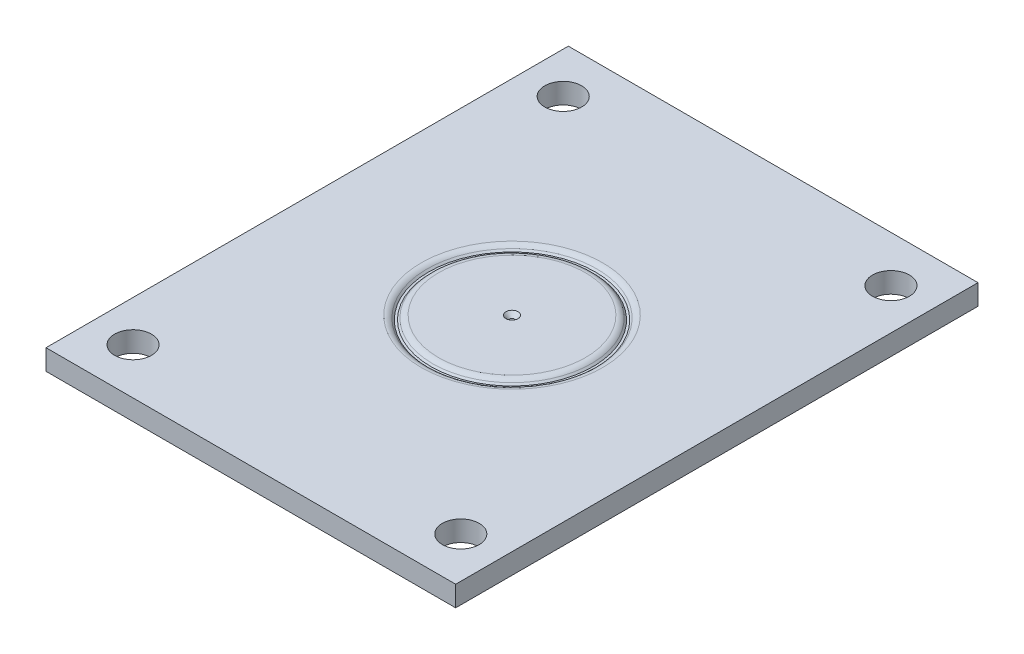
SolidWorks part; units mm, degrees
ref_plane "Front Plane" through (0, 0, 0) normal (0, 0, 1) x (1, 0, 0)
ref_plane "Top Plane" through (0, 0, 0) normal (0, 1, 0) x (1, 0, 0)
ref_plane "Right Plane" through (0, 0, 0) normal (1, 0, 0) x (0, 0, -1)
sketch "Sketch1" plane through (0, 0, 0) normal (0, 1, 0) x (1, 0, 0)
  line L1 (-82.6367, 47.4277) -> (117.3633, 47.4277)
  line L2 (-82.6367, 47.4277) -> (-82.6367, -207.5723)
  line L3 (-82.6367, -207.5723) -> (117.3633, -207.5723)
  line L4 (117.3633, 47.4277) -> (117.3633, -207.5723)
  dimension "D1" = 200
  dimension "D2" = 255
extrude "Boss-Extrude1" add sketch "Sketch1" along normal blind 10
sketch "Sketch2" plane through (0, 0, 0) normal (0, -1, 0) x (-1, 0, 0)
  circle A0 centre (-17.3633, -80.0723) radius 49.5926
extrude "Cut-Extrude1" cut sketch "Sketch2" against normal blind 3
sketch "Sketch3" plane through (0, 10, 0) normal (0, 1, 0) x (1, 0, 0)
  circle A0 centre (97.3633, -185.0723) radius 9
  circle A1 centre (-62.6367, 24.9277) radius 9
  circle A2 centre (-62.6367, -185.0723) radius 9
  circle A3 centre (97.3633, 24.9277) radius 9
  dimension "D3" = 18
extrude "Cut-Extrude2" cut sketch "Sketch3" against normal blind 69
sketch "Sketch4" plane through (0, 10, 0) normal (0, 1, 0) x (1, 0, 0)
  circle A0 centre (17.3633, -80.0723) radius 42.6389
  circle A1 centre (17.3633, -80.0723) radius 37.5406
extrude "Cut-Extrude3" cut sketch "Sketch4" against normal blind 2 draft 45
fillet "Fillet1" radius 4 1 edges at (17.3633, 10, 122.7112)
fillet "Fillet2" radius 4 1 edges at (17.3633, 10, 117.613)
sketch "Sketch5" plane through (0, 10, 0) normal (0, 1, 0) x (1, 0, 0)
  circle A0 centre (17.3633, -80.0723) radius 2.9523
extrude "Cut-Extrude4" cut sketch "Sketch5" against normal blind 2 draft 45
